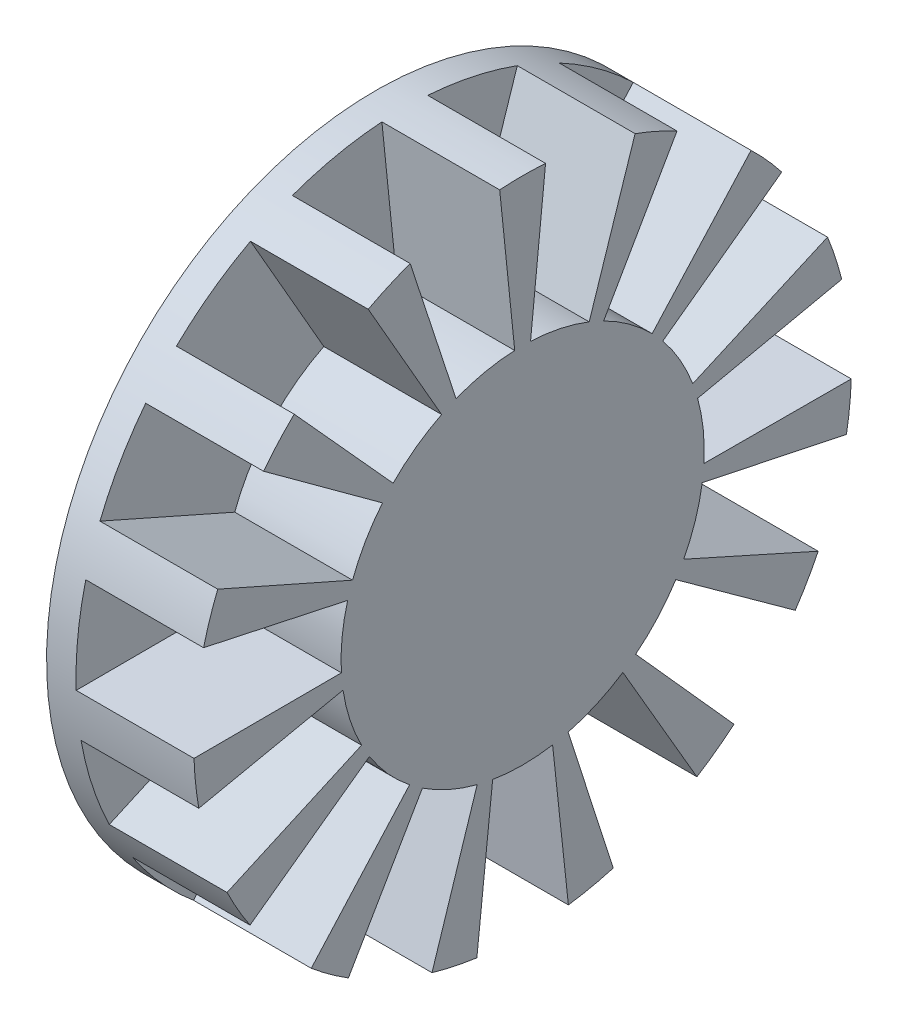
SolidWorks part; units mm, degrees
ref_plane "Front Plane" through (0, 0, 0) normal (0, 0, 1) x (1, 0, 0)
ref_plane "Top Plane" through (0, 0, 0) normal (0, 1, 0) x (1, 0, 0)
ref_plane "Right Plane" through (0, 0, 0) normal (1, 0, 0) x (0, 0, -1)
sketch "Sketch1" plane through (0, 0, 0) normal (1, 0, 0) x (0, 0, -1)
  circle A0 centre (0, 0) radius 33.5
  dimension "D1" = 67
extrude "Boss-Extrude1" add sketch "Sketch1" along normal blind 15
sketch "Sketch3" plane through (15, 0, 0) normal (1, 0, 0) x (0, 0, -1)
  line L0 (0, 0) -> (0, 33.5) construction
  line L1 (0, 0) -> (13.6257, 30.6038) construction
  line L2 (0, 0) -> (24.8954, 22.4159) construction
  line L3 (0, 0) -> (31.8604, 10.3521) construction
  line L4 (0, 0) -> (33.3165, -3.5017) construction
  line L5 (0, 0) -> (29.0119, -16.75) construction
  line L6 (0, 0) -> (19.6908, -27.1021) construction
  line L7 (0, 0) -> (6.965, -32.7679) construction
  line L8 (0, 0) -> (-6.965, -32.7679) construction
  line L9 (0, 0) -> (-19.6908, -27.1021) construction
  line L10 (0, 0) -> (-29.0119, -16.75) construction
  line L11 (0, 0) -> (-33.3165, -3.5017) construction
  line L12 (0, 0) -> (-31.8604, 10.3521) construction
  line L13 (0, 0) -> (-24.8954, 22.4159) construction
  line L14 (0, 0) -> (-13.6257, 30.6038) construction
  line L15 (0.807, 18.4824) -> (0, 0) construction
  line L16 (6.7803, 17.2127) -> (0, 0) construction
  line L17 (6.965, 32.7679) -> (0, 0) construction
  line L18 (2.3368, 33.4184) -> (0, 0) construction
  line L19 (11.4577, 31.4797) -> (0, 0) construction
  line L20 (2.3368, 33.4184) -> (0.807, 18.4824)
  line L21 (6.7803, 17.2127) -> (11.4577, 31.4797)
  line L22 (15.7273, 29.5787) -> (8.2547, 16.5563)
  line L23 (13.1951, 12.9668) -> (23.2711, 24.0979)
  line L24 (26.3984, 20.6247) -> (14.2751, 11.7674)
  line L25 (17.3284, 6.4788) -> (31.0607, 12.5493)
  line L26 (32.5049, 8.1044) -> (17.8272, 4.9439)
  line L27 (18.4655, -1.1294) -> (33.4796, -1.1691)
  line L28 (32.9911, -5.8172) -> (18.2968, -2.7345)
  line L29 (16.4097, -8.5423) -> (30.1096, -14.6854)
  line L30 (27.7728, -18.733) -> (15.6027, -9.94)
  line L31 (11.5165, -14.4783) -> (21.5334, -25.6625)
  line L32 (17.7523, -28.4096) -> (10.2108, -15.4269)
  line L33 (4.632, -17.9107) -> (9.2339, -32.2023)
  line L34 (4.6623, -33.174) -> (3.0534, -18.2463)
  line L35 (-3.0534, -18.2463) -> (-4.6623, -33.174)
  line L36 (-9.2339, -32.2023) -> (-4.632, -17.9107)
  line L37 (-10.2108, -15.4269) -> (-17.7523, -28.4096)
  line L38 (-21.5334, -25.6625) -> (-11.5165, -14.4783)
  line L39 (-15.6027, -9.94) -> (-27.7728, -18.733)
  line L40 (-30.1096, -14.6854) -> (-16.4097, -8.5423)
  line L41 (-18.2968, -2.7345) -> (-32.9911, -5.8172)
  line L42 (-33.4796, -1.1691) -> (-18.4655, -1.1294)
  line L43 (-17.8272, 4.9439) -> (-32.5049, 8.1044)
  line L44 (-31.0607, 12.5493) -> (-17.3284, 6.4788)
  line L45 (-14.2751, 11.7674) -> (-26.3984, 20.6247)
  line L46 (-23.2711, 24.0979) -> (-13.1951, 12.9668)
  line L47 (-8.2547, 16.5563) -> (-15.7273, 29.5787)
  line L48 (-11.4577, 31.4797) -> (-6.7803, 17.2127)
  line L49 (-0.807, 18.4824) -> (-2.3368, 33.4184)
  circle A0 centre (0, 0) radius 18.5 construction
  arc A1 (0, 33.5) -> (13.6257, 30.6038) centre (0, 0) cw construction
  arc A2 (2.3368, 33.4184) -> (11.4577, 31.4797) centre (0, 0) cw
  arc A3 (0.807, 18.4824) -> (6.7803, 17.2127) centre (0, 0) cw
  arc A4 (8.2547, 16.5563) -> (13.1951, 12.9668) centre (0, 0) cw
  arc A5 (15.7273, 29.5787) -> (23.2711, 24.0979) centre (0, 0) cw
  arc A6 (14.2751, 11.7674) -> (17.3284, 6.4788) centre (0, 0) cw
  arc A7 (26.3984, 20.6247) -> (31.0607, 12.5493) centre (0, 0) cw
  arc A8 (17.8272, 4.9439) -> (18.4655, -1.1294) centre (0, 0) cw
  arc A9 (32.5049, 8.1044) -> (33.4796, -1.1691) centre (0, 0) cw
  arc A10 (18.2968, -2.7345) -> (16.4097, -8.5423) centre (0, 0) cw
  arc A11 (32.9911, -5.8172) -> (30.1096, -14.6854) centre (0, 0) cw
  arc A12 (15.6027, -9.94) -> (11.5165, -14.4783) centre (0, 0) cw
  arc A13 (27.7728, -18.733) -> (21.5334, -25.6625) centre (0, 0) cw
  arc A14 (10.2108, -15.4269) -> (4.632, -17.9107) centre (0, 0) cw
  arc A15 (17.7523, -28.4096) -> (9.2339, -32.2023) centre (0, 0) cw
  arc A16 (3.0534, -18.2463) -> (-3.0534, -18.2463) centre (0, 0) cw
  arc A17 (4.6623, -33.174) -> (-4.6623, -33.174) centre (0, 0) cw
  arc A18 (-4.632, -17.9107) -> (-10.2108, -15.4269) centre (0, 0) cw
  arc A19 (-9.2339, -32.2023) -> (-17.7523, -28.4096) centre (0, 0) cw
  arc A20 (-11.5165, -14.4783) -> (-15.6027, -9.94) centre (0, 0) cw
  arc A21 (-21.5334, -25.6625) -> (-27.7728, -18.733) centre (0, 0) cw
  arc A22 (-16.4097, -8.5423) -> (-18.2968, -2.7345) centre (0, 0) cw
  arc A23 (-30.1096, -14.6854) -> (-32.9911, -5.8172) centre (0, 0) cw
  arc A24 (-18.4655, -1.1294) -> (-17.8272, 4.9439) centre (0, 0) cw
  arc A25 (-33.4796, -1.1691) -> (-32.5049, 8.1044) centre (0, 0) cw
  arc A26 (-17.3284, 6.4788) -> (-14.2751, 11.7674) centre (0, 0) cw
  arc A27 (-31.0607, 12.5493) -> (-26.3984, 20.6247) centre (0, 0) cw
  arc A28 (-13.1951, 12.9668) -> (-8.2547, 16.5563) centre (0, 0) cw
  arc A29 (-23.2711, 24.0979) -> (-15.7273, 29.5787) centre (0, 0) cw
  arc A30 (-6.7803, 17.2127) -> (-0.807, 18.4824) centre (0, 0) cw
  arc A31 (-11.4577, 31.4797) -> (-2.3368, 33.4184) centre (0, 0) cw
  point P17 (0, 0)
  point P80 (-1.3731, -4.0422)
  dimension "D1" = 2.5
  dimension "D2" = 2.5
  dimension "D3" = 4
  dimension "D4" = 4
  dimension "D5" = 15.0142
  dimension "D6" = 15.0142
  dimension "D7" = 15.0142
  dimension "D8" = 14.936
extrude "Cut-Extrude1" cut sketch "Sketch3" against normal blind 12
